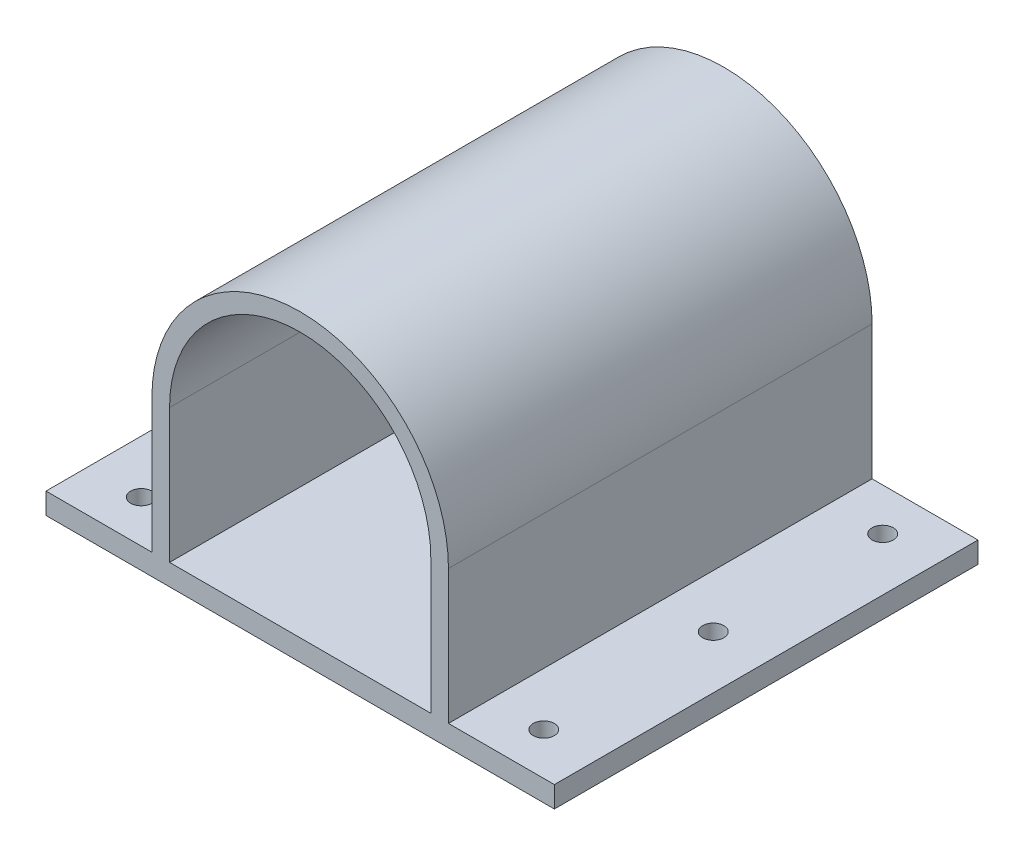
SolidWorks part; units mm, degrees
ref_plane "Front Plane" through (0, 0, 0) normal (0, 0, 1) x (1, 0, 0)
ref_plane "Top Plane" through (0, 0, 0) normal (0, 1, 0) x (1, 0, 0)
ref_plane "Right Plane" through (0, 0, 0) normal (1, 0, 0) x (0, 0, -1)
sketch "Sketch1" plane through (0, 0, 0) normal (0, 0, 1) x (1, 0, 0)
  line L0 (-21, 0) -> (-21, -19)
  line L1 (-21, -19) -> (-36, -19)
  line L2 (-36, -19) -> (-36, -22)
  line L3 (-36, -22) -> (36, -22)
  line L4 (36, -22) -> (36, -19)
  line L5 (36, -19) -> (21, -19)
  line L6 (21, -19) -> (21, 0)
  line L7 (0, 0) -> (0, -7) construction
  line L8 (0, 0) -> (-15.5, 0) construction
  arc A0 (21, 0) -> (-21, 0) centre (0, 0) ccw
  circle A1 centre (0, -7) radius 6.15
  circle A2 centre (-15.5, 0) radius 1.65
  circle A3 centre (-7.75, 13.4234) radius 1.65
  circle A4 centre (7.75, 13.4234) radius 1.65
  circle A5 centre (15.5, 0) radius 1.65
  circle A6 centre (7.75, -13.4234) radius 1.65
  circle A7 centre (-7.75, -13.4234) radius 1.65
  point P27 (0, 0)
  dimension "D1" = 42
  dimension "D6" = 12.3
  dimension "D7" = 3.3
  dimension "D2" = 7
  dimension "D3" = 15
  dimension "D4" = 72
  dimension "D5" = 3
  dimension "D8" = 15.5
  dimension "D9" = 6
extrude "Boss-Extrude1" add sketch "Sketch1" along normal blind 60
sketch "Sketch2" plane through (0, 0, 60) normal (0, 0, 1) x (1, 0, 0)
  line L0 (-18.5, 0) -> (-18.5, -19)
  line L2 (-18.5, -19) -> (18.5, -19)
  line L3 (18.5, -19) -> (18.5, 0)
  line L5 (-21, -19) -> (-36, -19) construction
  arc A0 (18.5, 0) -> (-18.5, 0) centre (0, 0) ccw
  arc A1 (-18.5, 0) -> (18.5, 0) centre (0, 0) ccw construction
  dimension "D1" = 37
extrude "Cut-Extrude1" cut sketch "Sketch2" against normal blind 57
sketch "Sketch3" plane through (0, -19, 0) normal (0, 1, 0) x (1, 0, 0)
  line L0 (0, 0) -> (0, -60) construction
  line L1 (-21, -60) -> (21, -60) construction
  line L2 (-28.5, 0) -> (-28.5, -60) construction
  line L3 (-21, 0) -> (-36, 0) construction
  line L4 (-21, -60) -> (-36, -60) construction
  circle A0 centre (-28.5, -30) radius 1.5
  circle A1 centre (-28.5, -6) radius 1.5
  circle A2 centre (-28.5, -54) radius 1.5
  circle A3 centre (28.5, -54) radius 1.5
  circle A4 centre (28.5, -6) radius 1.5
  circle A5 centre (28.5, -30) radius 1.5
  dimension "D1" = 24
  dimension "D2" = 24
  dimension "D3" = 3
extrude "Cut-Extrude2" cut sketch "Sketch3" against normal through all
